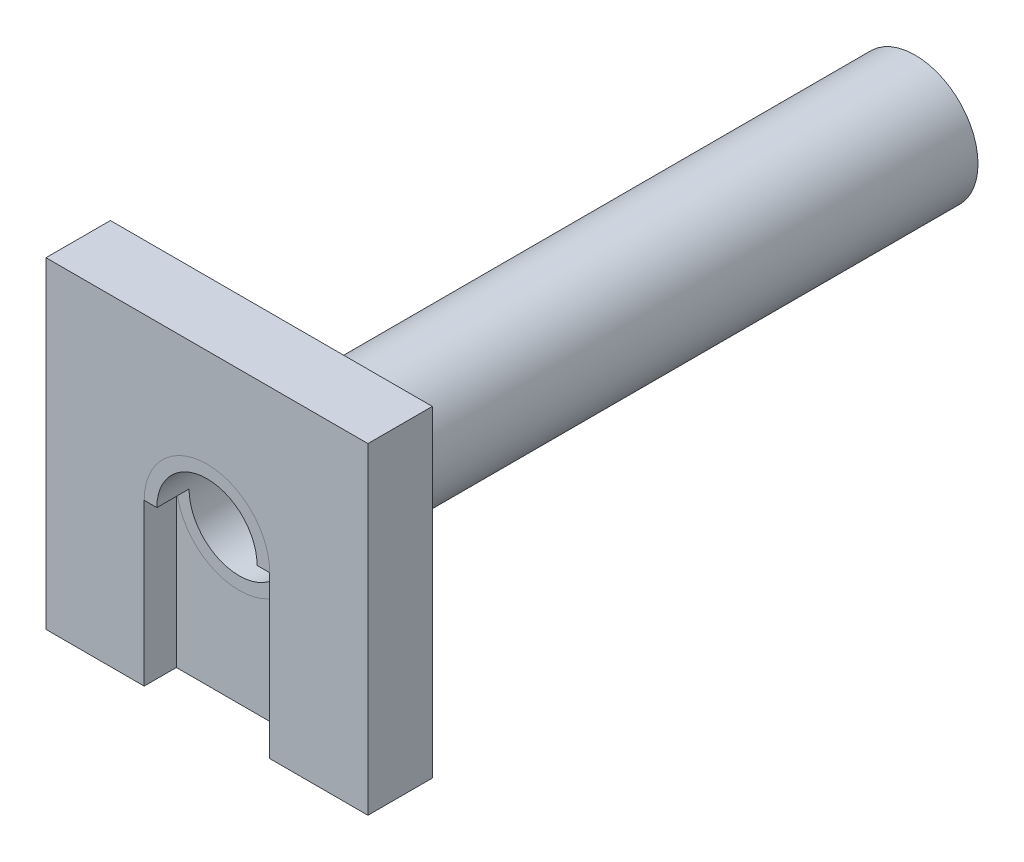
SolidWorks part; units mm, degrees
ref_plane "Front Plane" through (0, 0, 0) normal (0, 0, 1) x (1, 0, 0)
ref_plane "Top Plane" through (0, 0, 0) normal (0, 1, 0) x (1, 0, 0)
ref_plane "Right Plane" through (0, 0, 0) normal (1, 0, 0) x (0, 0, -1)
sketch "Sketch1" plane through (0, 0, 0) normal (0, 0, 1) x (1, 0, 0)
  circle A0 centre (0, 5) radius 4.953
  circle A1 centre (0, 5) radius 3.953
  dimension "D1" = 1
extrude "Boss-Extrude1" add sketch "Sketch1" along normal blind 55.88
sketch "Sketch2" plane through (0, 0, 55.88) normal (0, 0, 1) x (1, 0, 0)
  line L0 (12.7, -7.7) -> (-12.7, 17.7) construction
  line L1 (12.7, -7.7) -> (-12.7, -7.7)
  line L2 (12.7, -7.7) -> (12.7, 17.7)
  line L3 (12.7, 17.7) -> (-12.7, 17.7)
  line L4 (-12.7, -7.7) -> (-12.7, 17.7)
  line L5 (-12.7, -7.7) -> (-31.2747, -29.0398)
  line L6 (12.7, 17.7) -> (-12.7, -7.7) construction
  circle A1 centre (0, 5) radius 3.953 construction
  point P4 (18.7642, 1.1056)
  point P7 (0, 5)
  circle M1 centre (0, 5) radius 4.953
  dimension "D1" = 25.4
  dimension "D2" = 25.4
extrude "Boss-Extrude2" add sketch "Sketch2" against normal blind 5.08 separate body contours L4 L1 L2 L3 M1
sketch "Sketch4" plane through (0, 0, 55.88) normal (0, 0, -1) x (-1, 0, 0)
  line L0 (-4.953, 5) -> (-4.953, -7.7)
  line L1 (-12.7, -7.7) -> (12.7, -7.7) construction
  line L2 (-4.953, -7.7) -> (4.953, -7.7)
  line L3 (4.953, -7.7) -> (4.953, 5)
  line L4 (4.953, 5) -> (-4.953, 5)
  circle A0 centre (0, 5) radius 4.953 construction
extrude "Cut-Extrude1" cut sketch "Sketch4" along normal blind 2.54
